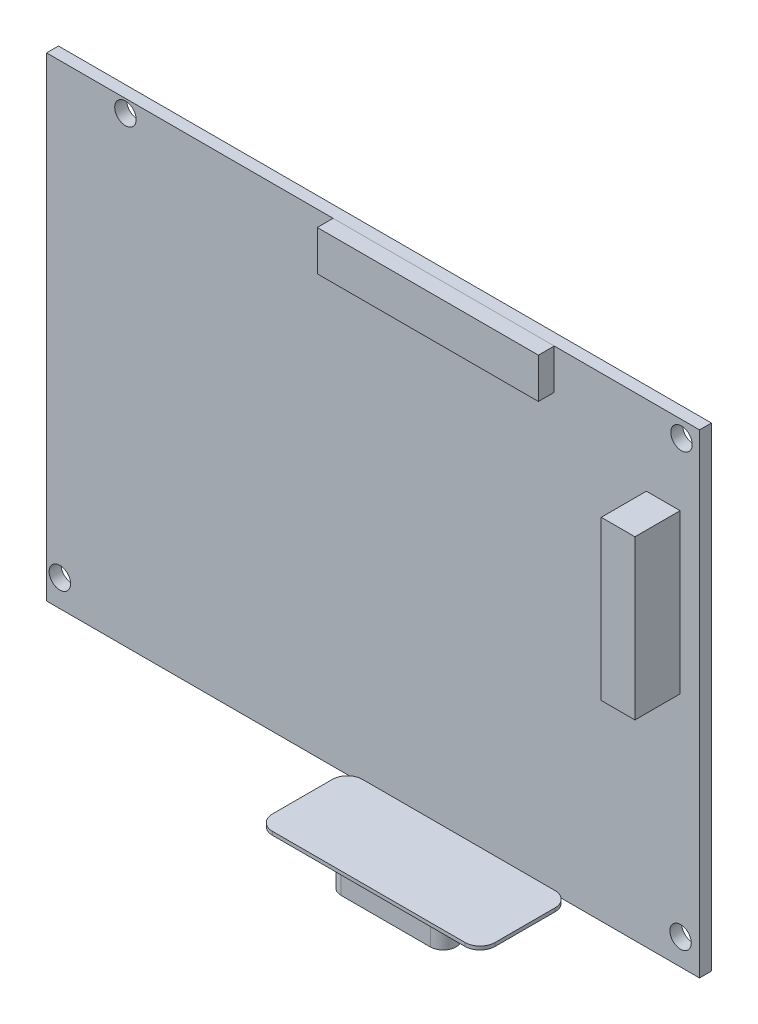
SolidWorks part; units mm, degrees
ref_plane "Front Plane" through (0, 0, 0) normal (0, 0, 1) x (1, 0, 0)
ref_plane "Top Plane" through (0, 0, 0) normal (0, 1, 0) x (1, 0, 0)
ref_plane "Right Plane" through (0, 0, 0) normal (1, 0, 0) x (0, 0, -1)
sketch "Sketch1" plane through (0, 0, 0) normal (0, 0, 1) x (1, 0, 0)
  line L1 (-45.2628, -32.9057) -> (45.2628, -32.9057)
  line L2 (-45.2628, -32.9057) -> (-45.2628, 32.9057)
  line L3 (-45.2628, 32.9057) -> (45.2628, 32.9057)
  line L4 (45.2628, -32.9057) -> (45.2628, 32.9057)
  line L5 (-45.2628, -32.9057) -> (45.2628, 32.9057) construction
  line L6 (-45.2628, 32.9057) -> (45.2628, -32.9057) construction
  circle A0 centre (-34.3281, 31.115) radius 1.4859
  circle A1 centre (-43.4213, -29.1846) radius 1.4859
  circle A2 centre (42.7609, 30.6324) radius 1.4859
  circle A3 centre (42.6339, -29.2862) radius 1.4859
  point P0 (0, 0)
  point P14 (-34.3281, 32.6009)
  point P15 (-35.814, 31.115)
  point P16 (-43.4213, -30.6705)
  point P17 (-44.9072, -29.1846)
  point P18 (44.1198, -29.2862)
  point P19 (42.6339, -30.7721)
  point P20 (42.7609, 32.1183)
  point P21 (44.2468, 30.6324)
  dimension "D5" = 2.9718
  dimension "D1" = 90.5256
  dimension "D2" = 65.8114
  dimension "D3" = 9.4488
  dimension "D4" = 0.3048
  dimension "D6" = 2.2352
  dimension "D7" = 0.3556
  dimension "D8" = 2.1336
  dimension "D9" = 1.143
  dimension "D10" = 1.016
  dimension "D11" = 0.7874
extrude "Boss-Extrude1" add sketch "Sketch1" against normal blind 1.651
sketch "Sketch2" plane through (0, -32.9057, 0) normal (0, -1, 0) x (1, 0, 0)
  line L0 (45.2628, -1.651) -> (45.2628, 0) construction
  line L1 (-1.4732, 0) -> (25.2222, 0)
  line L2 (-3.556, 2.0828) -> (-3.556, 10.3886)
  line L3 (-1.4732, 12.4714) -> (25.2222, 12.4714)
  line L4 (27.305, 2.0828) -> (27.305, 10.3886)
  line L5 (45.2628, -1.651) -> (45.2628, 0) construction
  line L6 (-45.2628, 0) -> (45.2628, 0) construction
  arc A0 (25.2222, 0) -> (27.305, 2.0828) centre (25.2222, 2.0828) ccw
  arc A1 (25.2222, 12.4714) -> (27.305, 10.3886) centre (25.2222, 10.3886) cw
  arc A2 (-3.556, 10.3886) -> (-1.4732, 12.4714) centre (-1.4732, 10.3886) cw
  arc A3 (-1.4732, 0) -> (-3.556, 2.0828) centre (-1.4732, 2.0828) cw
  point P15 (27.305, 12.4714)
  point P18 (-3.556, 12.4714)
  point P21 (-3.556, 0)
  dimension "D4" = 2.0828
  dimension "D1" = 17.9578
  dimension "D2" = 30.861
  dimension "D3" = 12.4714
extrude "Boss-Extrude2" add sketch "Sketch2" against normal blind 0.4826 separate body
sketch "Sketch3" plane through (0, -32.9057, 0) normal (0, -1, 0) x (1, 0, 0)
  line L0 (5.6949, 10.1092) -> (18.0541, 10.1092)
  line L1 (19.7739, 7.88) -> (18.6743, 3.689)
  line L2 (16.9545, 2.3622) -> (6.7945, 2.3622)
  line L3 (5.0747, 3.689) -> (3.9751, 7.88)
  line L4 (11.8745, 10.1092) -> (11.8745, 12.4714) construction
  line L5 (25.2222, 12.4714) -> (-1.4732, 12.4714) construction
  line L6 (11.8745, 0) -> (11.8745, 2.3622) construction
  line L7 (-1.4732, 0) -> (25.2222, 0) construction
  arc A0 (18.6743, 3.689) -> (16.9545, 2.3622) centre (16.9545, 4.1402) cw
  arc A1 (6.7945, 2.3622) -> (5.0747, 3.689) centre (6.7945, 4.1402) cw
  arc A2 (18.0541, 10.1092) -> (19.7739, 7.88) centre (18.0541, 8.3312) cw
  arc A3 (5.6949, 10.1092) -> (3.9751, 7.88) centre (5.6949, 8.3312) ccw
  dimension "D2" = 1.778
  dimension "D1" = 7.747
  dimension "D3" = 15.7988
  dimension "D4" = 10.16
extrude "Boss-Extrude3" add sketch "Sketch3" along normal blind 4.826
sketch "Sketch4" plane through (0, 0, 0) normal (0, 0, 1) x (1, 0, 0)
  line L0 (45.2628, 32.9057) -> (-45.2628, 32.9057) construction
  line L1 (-5.5372, 32.9057) -> (25.1206, 32.9057)
  line L2 (-5.5372, 32.9057) -> (-5.5372, 27.3431)
  line L3 (-5.5372, 27.3431) -> (25.1206, 27.3431)
  line L4 (25.1206, 32.9057) -> (25.1206, 27.3431)
  line L5 (45.2628, -32.9057) -> (45.2628, 32.9057) construction
  dimension "D1" = 20.1422
  dimension "D2" = 30.6578
  dimension "D3" = 5.5626
extrude "Boss-Extrude4" add sketch "Sketch4" along normal blind 2.1971 separate body
sketch "Sketch5" plane through (0, 0, 0) normal (0, 0, 1) x (1, 0, 0)
  line L0 (45.2628, 32.9057) -> (-45.2628, 32.9057) construction
  line L1 (37.8968, 21.8567) -> (42.5704, 21.8567)
  line L2 (37.8968, 21.8567) -> (37.8968, -0.1397)
  line L3 (37.8968, -0.1397) -> (42.5704, -0.1397)
  line L4 (42.5704, 21.8567) -> (42.5704, -0.1397)
  line L5 (45.2628, -32.9057) -> (45.2628, 32.9057) construction
  dimension "D1" = 21.9964
  dimension "D2" = 11.049
  dimension "D3" = 4.6736
  dimension "D4" = 7.366
extrude "Boss-Extrude5" add sketch "Sketch5" along normal blind 6.2611 separate body
